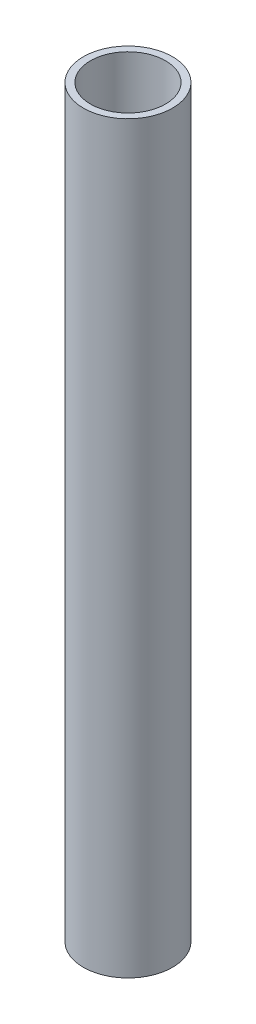
SolidWorks part; units mm, degrees
ref_plane "Front Plane" through (0, 0, 0) normal (0, 0, 1) x (1, 0, 0)
ref_plane "Top Plane" through (0, 0, 0) normal (0, 1, 0) x (1, 0, 0)
ref_plane "Right Plane" through (0, 0, 0) normal (1, 0, 0) x (0, 0, -1)
sketch "Sketch1" plane through (0, 0, 0) normal (0, 1, 0) x (1, 0, 0)
  circle A0 centre (0, 0) radius 6.35
  circle A1 centre (0, 0) radius 5.35
extrude "Boss-Extrude1" add sketch "Sketch1" along normal blind 106
